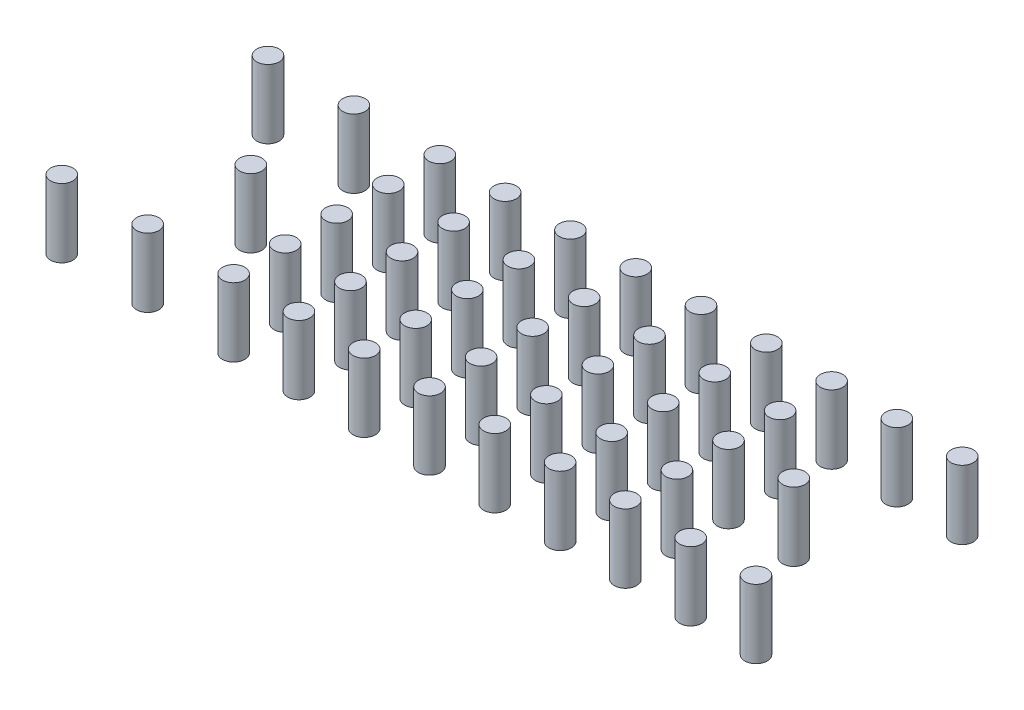
SolidWorks part; units mm, degrees
ref_plane "Front Plane" through (0, 0, 0) normal (0, 0, 1) x (1, 0, 0)
ref_plane "Top Plane" through (0, 0, 0) normal (0, 1, 0) x (1, 0, 0)
ref_plane "Right Plane" through (0, 0, 0) normal (1, 0, 0) x (0, 0, -1)
sketch "Sketch2" plane through (0, 0, 0) normal (0, 1, 0) x (1, 0, 0)
  line L0 (1.9, 0) -> (3.35, 0) construction
  line L1 (0, 0) -> (1.45, 0) construction
  line L2 (0, 0) -> (0, -1.25) construction
  line L3 (0, -1.25) -> (1.45, -1.25) construction
  line L4 (1.45, 0) -> (1.45, -1.25) construction
  line L5 (1.9, 0) -> (1.9, -1.25) construction
  line L6 (1.9, -1.25) -> (3.35, -1.25) construction
  line L7 (3.35, 0) -> (3.35, -1.25) construction
  line L8 (3.8, 0) -> (5.25, 0) construction
  line L9 (3.8, 0) -> (3.8, -1.25) construction
  line L10 (3.8, -1.25) -> (5.25, -1.25) construction
  line L11 (5.25, 0) -> (5.25, -1.25) construction
  line L12 (5.7, 0) -> (7.15, 0) construction
  line L13 (5.7, 0) -> (5.7, -1.25) construction
  line L14 (5.7, -1.25) -> (7.15, -1.25) construction
  line L15 (7.15, 0) -> (7.15, -1.25) construction
  line L16 (7.6, 0) -> (9.05, 0) construction
  line L17 (7.6, 0) -> (7.6, -1.25) construction
  line L18 (7.6, -1.25) -> (9.05, -1.25) construction
  line L19 (9.05, 0) -> (9.05, -1.25) construction
  line L20 (9.5, 0) -> (10.95, 0) construction
  line L21 (9.5, 0) -> (9.5, -1.25) construction
  line L22 (9.5, -1.25) -> (10.95, -1.25) construction
  line L23 (10.95, 0) -> (10.95, -1.25) construction
  line L24 (11.4, 0) -> (12.85, 0) construction
  line L25 (11.4, 0) -> (11.4, -1.25) construction
  line L26 (11.4, -1.25) -> (12.85, -1.25) construction
  line L27 (12.85, 0) -> (12.85, -1.25) construction
  line L28 (13.3, 0) -> (14.75, 0) construction
  line L29 (13.3, 0) -> (13.3, -1.25) construction
  line L30 (13.3, -1.25) -> (14.75, -1.25) construction
  line L31 (14.75, 0) -> (14.75, -1.25) construction
  line L32 (15.2, 0) -> (16.65, 0) construction
  line L33 (15.2, 0) -> (15.2, -1.25) construction
  line L34 (15.2, -1.25) -> (16.65, -1.25) construction
  line L35 (16.65, 0) -> (16.65, -1.25) construction
  line L36 (1.9, 1.5) -> (3.35, 1.5) construction
  line L37 (1.9, 1.5) -> (1.9, 0.25) construction
  line L38 (1.9, 0.25) -> (3.35, 0.25) construction
  line L39 (3.35, 1.5) -> (3.35, 0.25) construction
  line L40 (3.8, 1.5) -> (5.25, 1.5) construction
  line L41 (3.8, 1.5) -> (3.8, 0.25) construction
  line L42 (3.8, 0.25) -> (5.25, 0.25) construction
  line L43 (5.25, 1.5) -> (5.25, 0.25) construction
  line L44 (5.7, 1.5) -> (7.15, 1.5) construction
  line L45 (5.7, 1.5) -> (5.7, 0.25) construction
  line L46 (5.7, 0.25) -> (7.15, 0.25) construction
  line L47 (7.15, 1.5) -> (7.15, 0.25) construction
  line L48 (7.6, 1.5) -> (9.05, 1.5) construction
  line L49 (7.6, 1.5) -> (7.6, 0.25) construction
  line L50 (7.6, 0.25) -> (9.05, 0.25) construction
  line L51 (9.05, 1.5) -> (9.05, 0.25) construction
  line L52 (9.5, 1.5) -> (10.95, 1.5) construction
  line L53 (9.5, 1.5) -> (9.5, 0.25) construction
  line L54 (9.5, 0.25) -> (10.95, 0.25) construction
  line L55 (10.95, 1.5) -> (10.95, 0.25) construction
  line L56 (11.4, 1.5) -> (12.85, 1.5) construction
  line L57 (11.4, 1.5) -> (11.4, 0.25) construction
  line L58 (11.4, 0.25) -> (12.85, 0.25) construction
  line L59 (12.85, 1.5) -> (12.85, 0.25) construction
  line L60 (13.3, 1.5) -> (14.75, 1.5) [skipped]
  line L61 (13.3, 1.5) -> (13.3, 0.25) [skipped]
  line L62 (13.3, 0.25) -> (14.75, 0.25) [skipped]
  line L63 (14.75, 1.5) -> (14.75, 0.25) [skipped]
  line L64 (15.2, 1.5) -> (16.65, 1.5) [skipped]
  line L65 (15.2, 1.5) -> (15.2, 0.25) [skipped]
  line L66 (15.2, 0.25) -> (16.65, 0.25) [skipped]
  line L67 (16.65, 1.5) -> (16.65, 0.25) [skipped]
  line L68 (1.9, 3) -> (3.35, 3) construction
  line L69 (1.9, 3) -> (1.9, 1.75) construction
  line L70 (1.9, 1.75) -> (3.35, 1.75) construction
  line L71 (3.35, 3) -> (3.35, 1.75) construction
  line L72 (3.8, 3) -> (5.25, 3) construction
  line L73 (3.8, 3) -> (3.8, 1.75) construction
  line L74 (3.8, 1.75) -> (5.25, 1.75) construction
  line L75 (5.25, 3) -> (5.25, 1.75) construction
  line L76 (5.7, 3) -> (7.15, 3) construction
  line L77 (5.7, 3) -> (5.7, 1.75) construction
  line L78 (5.7, 1.75) -> (7.15, 1.75) construction
  line L79 (7.15, 3) -> (7.15, 1.75) construction
  line L80 (7.6, 3) -> (9.05, 3) construction
  line L81 (7.6, 3) -> (7.6, 1.75) construction
  line L82 (7.6, 1.75) -> (9.05, 1.75) construction
  line L83 (9.05, 3) -> (9.05, 1.75) construction
  line L84 (9.5, 3) -> (10.95, 3) construction
  line L85 (9.5, 3) -> (9.5, 1.75) construction
  line L86 (9.5, 1.75) -> (10.95, 1.75) construction
  line L87 (10.95, 3) -> (10.95, 1.75) construction
  line L88 (11.4, 3) -> (12.85, 3) construction
  line L89 (11.4, 3) -> (11.4, 1.75) construction
  line L90 (11.4, 1.75) -> (12.85, 1.75) construction
  line L91 (12.85, 3) -> (12.85, 1.75) construction
  line L92 (13.3, 3) -> (14.75, 3) construction
  line L93 (13.3, 3) -> (13.3, 1.75) construction
  line L94 (13.3, 1.75) -> (14.75, 1.75) construction
  line L95 (14.75, 3) -> (14.75, 1.75) construction
  line L96 (15.2, 3) -> (16.65, 3) [skipped]
  line L97 (15.2, 3) -> (15.2, 1.75) [skipped]
  line L98 (15.2, 1.75) -> (16.65, 1.75) [skipped]
  line L99 (16.65, 3) -> (16.65, 1.75) [skipped]
  line L100 (1.9, 4.5) -> (3.35, 4.5) construction
  line L101 (1.9, 4.5) -> (1.9, 3.25) construction
  line L102 (1.9, 3.25) -> (3.35, 3.25) construction
  line L103 (3.35, 4.5) -> (3.35, 3.25) construction
  line L104 (3.8, 4.5) -> (5.25, 4.5) construction
  line L105 (3.8, 4.5) -> (3.8, 3.25) construction
  line L106 (3.8, 3.25) -> (5.25, 3.25) construction
  line L107 (5.25, 4.5) -> (5.25, 3.25) construction
  line L108 (5.7, 4.5) -> (7.15, 4.5) construction
  line L109 (5.7, 4.5) -> (5.7, 3.25) construction
  line L110 (5.7, 3.25) -> (7.15, 3.25) construction
  line L111 (7.15, 4.5) -> (7.15, 3.25) construction
  line L112 (7.6, 4.5) -> (9.05, 4.5) construction
  line L113 (7.6, 4.5) -> (7.6, 3.25) construction
  line L114 (7.6, 3.25) -> (9.05, 3.25) construction
  line L115 (9.05, 4.5) -> (9.05, 3.25) construction
  line L116 (9.5, 4.5) -> (10.95, 4.5) construction
  line L117 (9.5, 4.5) -> (9.5, 3.25) construction
  line L118 (9.5, 3.25) -> (10.95, 3.25) construction
  line L119 (10.95, 4.5) -> (10.95, 3.25) construction
  line L120 (11.4, 4.5) -> (12.85, 4.5) construction
  line L121 (11.4, 4.5) -> (11.4, 3.25) construction
  line L122 (11.4, 3.25) -> (12.85, 3.25) construction
  line L123 (12.85, 4.5) -> (12.85, 3.25) construction
  line L124 (13.3, 4.5) -> (14.75, 4.5) [skipped]
  line L125 (13.3, 4.5) -> (13.3, 3.25) [skipped]
  line L126 (13.3, 3.25) -> (14.75, 3.25) [skipped]
  line L127 (14.75, 4.5) -> (14.75, 3.25) [skipped]
  line L128 (15.2, 4.5) -> (16.65, 4.5) [skipped]
  line L129 (15.2, 4.5) -> (15.2, 3.25) [skipped]
  line L130 (15.2, 3.25) -> (16.65, 3.25) [skipped]
  line L131 (16.65, 4.5) -> (16.65, 3.25) [skipped]
  line L132 (1.9, 6) -> (3.35, 6) construction
  line L133 (1.9, 6) -> (1.9, 4.75) construction
  line L134 (1.9, 4.75) -> (3.35, 4.75) construction
  line L135 (3.35, 6) -> (3.35, 4.75) construction
  line L136 (3.8, 6) -> (5.25, 6) construction
  line L137 (3.8, 6) -> (3.8, 4.75) construction
  line L138 (3.8, 4.75) -> (5.25, 4.75) construction
  line L139 (5.25, 6) -> (5.25, 4.75) construction
  line L140 (5.7, 6) -> (7.15, 6) construction
  line L141 (5.7, 6) -> (5.7, 4.75) construction
  line L142 (5.7, 4.75) -> (7.15, 4.75) construction
  line L143 (7.15, 6) -> (7.15, 4.75) construction
  line L144 (7.6, 6) -> (9.05, 6) construction
  line L145 (7.6, 6) -> (7.6, 4.75) construction
  line L146 (7.6, 4.75) -> (9.05, 4.75) construction
  line L147 (9.05, 6) -> (9.05, 4.75) construction
  line L148 (9.5, 6) -> (10.95, 6) construction
  line L149 (9.5, 6) -> (9.5, 4.75) construction
  line L150 (9.5, 4.75) -> (10.95, 4.75) construction
  line L151 (10.95, 6) -> (10.95, 4.75) construction
  line L152 (11.4, 6) -> (12.85, 6) construction
  line L153 (11.4, 6) -> (11.4, 4.75) construction
  line L154 (11.4, 4.75) -> (12.85, 4.75) construction
  line L155 (12.85, 6) -> (12.85, 4.75) construction
  line L156 (13.3, 6) -> (14.75, 6) construction
  line L157 (13.3, 6) -> (13.3, 4.75) construction
  line L158 (13.3, 4.75) -> (14.75, 4.75) construction
  line L159 (14.75, 6) -> (14.75, 4.75) construction
  line L160 (15.2, 6) -> (16.65, 6) construction
  line L161 (15.2, 6) -> (15.2, 4.75) construction
  line L162 (15.2, 4.75) -> (16.65, 4.75) construction
  line L163 (16.65, 6) -> (16.65, 4.75) construction
  line L164 (0, 1.5) -> (1.45, 1.5) construction
  line L165 (0, 1.5) -> (0, 0.25) construction
  line L166 (0, 0.25) -> (1.45, 0.25) construction
  line L167 (1.45, 1.5) -> (1.45, 0.25) construction
  line L168 (0, 3) -> (1.45, 3) construction
  line L169 (0, 3) -> (0, 1.75) construction
  line L170 (0, 1.75) -> (1.45, 1.75) construction
  line L171 (1.45, 3) -> (1.45, 1.75) construction
  line L172 (0, 4.5) -> (1.45, 4.5) construction
  line L173 (0, 4.5) -> (0, 3.25) construction
  line L174 (0, 3.25) -> (1.45, 3.25) construction
  line L175 (1.45, 4.5) -> (1.45, 3.25) construction
  line L176 (0, 6) -> (1.45, 6) construction
  line L177 (0, 6) -> (0, 4.75) construction
  line L178 (0, 4.75) -> (1.45, 4.75) construction
  line L179 (1.45, 6) -> (1.45, 4.75) construction
  line L180 (1.45, 0) -> (0, -1.25) construction
  line L181 (3.35, 0) -> (1.9, -1.25) construction
  line L182 (5.25, 0) -> (3.8, -1.25) construction
  line L183 (7.15, 0) -> (5.7, -1.25) construction
  line L184 (9.05, 0) -> (7.6, -1.25) construction
  line L185 (10.95, 0) -> (9.5, -1.25) construction
  line L186 (12.85, 0) -> (11.4, -1.25) construction
  line L187 (14.75, 0) -> (13.3, -1.25) construction
  line L188 (16.65, 0) -> (15.2, -1.25) construction
  line L189 (3.35, 1.5) -> (1.9, 0.25) construction
  line L190 (5.25, 1.5) -> (3.8, 0.25) construction
  line L191 (7.15, 1.5) -> (5.7, 0.25) construction
  line L192 (9.05, 1.5) -> (7.6, 0.25) construction
  line L193 (10.95, 1.5) -> (9.5, 0.25) construction
  line L194 (12.85, 1.5) -> (11.4, 0.25) construction
  line L195 (-1.05, 0) -> (-2.5, -1.25) construction
  line L196 (-1.05, -1.25) -> (-2.5, -1.25) construction
  line L197 (3.35, 3) -> (1.9, 1.75) construction
  line L198 (5.25, 3) -> (3.8, 1.75) construction
  line L199 (7.15, 3) -> (5.7, 1.75) construction
  line L200 (9.05, 3) -> (7.6, 1.75) construction
  line L201 (10.95, 3) -> (9.5, 1.75) construction
  line L202 (12.85, 3) -> (11.4, 1.75) construction
  line L203 (14.75, 3) -> (13.3, 1.75) construction
  line L204 (-1.05, -1.25) -> (-1.05, 0) construction
  line L205 (3.35, 4.5) -> (1.9, 3.25) construction
  line L206 (5.25, 4.5) -> (3.8, 3.25) construction
  line L207 (7.15, 4.5) -> (5.7, 3.25) construction
  line L208 (9.05, 4.5) -> (7.6, 3.25) construction
  line L209 (10.95, 4.5) -> (9.5, 3.25) construction
  line L210 (12.85, 4.5) -> (11.4, 3.25) construction
  line L211 (-1.05, 0) -> (-2.5, 0) construction
  line L212 (-2.5, -1.25) -> (-2.5, 0) construction
  line L213 (3.35, 6) -> (1.9, 4.75) construction
  line L214 (5.25, 6) -> (3.8, 4.75) construction
  line L215 (7.15, 6) -> (5.7, 4.75) construction
  line L216 (9.05, 6) -> (7.6, 4.75) construction
  line L217 (10.95, 6) -> (9.5, 4.75) construction
  line L218 (12.85, 6) -> (11.4, 4.75) construction
  line L219 (14.75, 6) -> (13.3, 4.75) construction
  line L220 (16.65, 6) -> (15.2, 4.75) construction
  line L221 (1.45, 1.5) -> (0, 0.25) construction
  line L222 (1.45, 3) -> (0, 1.75) construction
  line L223 (1.45, 4.5) -> (0, 3.25) construction
  line L224 (1.45, 6) -> (0, 4.75) construction
  line L225 (14.75, 1.5) -> (13.3, 0.25) construction
  line L226 (16.65, 1.5) -> (15.2, 0.25) construction
  line L227 (16.65, 3) -> (15.2, 1.75) construction
  line L228 (14.75, 4.5) -> (13.3, 3.25) construction
  line L229 (16.65, 4.5) -> (15.2, 3.25) construction
  line L230 (-3.55, 0) -> (-5, -1.25) construction
  line L231 (-3.55, -1.25) -> (-5, -1.25) construction
  line L232 (-3.55, -1.25) -> (-3.55, 0) construction
  line L233 (-3.55, 0) -> (-5, 0) construction
  line L234 (-5, -1.25) -> (-5, 0) construction
  line L235 (-3.55, 1.5) -> (-5, 0.25) construction
  line L236 (-3.55, 0.25) -> (-5, 0.25) construction
  line L237 (-3.55, 0.25) -> (-3.55, 1.5) construction
  line L238 (-3.55, 1.5) -> (-5, 1.5) construction
  line L239 (-5, 0.25) -> (-5, 1.5) construction
  line L240 (-3.55, 3) -> (-5, 1.75) construction
  line L241 (-3.55, 1.75) -> (-5, 1.75) construction
  line L242 (-3.55, 1.75) -> (-3.55, 3) construction
  line L243 (-3.55, 3) -> (-5, 3) construction
  line L244 (-5, 1.75) -> (-5, 3) construction
  line L245 (-3.55, 4.5) -> (-5, 3.25) construction
  line L246 (-3.55, 3.25) -> (-5, 3.25) construction
  line L247 (-3.55, 3.25) -> (-3.55, 4.5) construction
  line L248 (-3.55, 4.5) -> (-5, 4.5) construction
  line L249 (-5, 3.25) -> (-5, 4.5) construction
  line L250 (-3.55, 6) -> (-5, 4.75) construction
  line L251 (-3.55, 4.75) -> (-5, 4.75) construction
  line L252 (-3.55, 4.75) -> (-3.55, 6) construction
  line L253 (-3.55, 6) -> (-5, 6) construction
  line L254 (-5, 4.75) -> (-5, 6) construction
  line L255 (-1.05, 1.5) -> (-2.5, 0.25) construction
  line L256 (-1.05, 0.25) -> (-2.5, 0.25) construction
  line L257 (-1.05, 0.25) -> (-1.05, 1.5) construction
  line L258 (-1.05, 1.5) -> (-2.5, 1.5) construction
  line L259 (-2.5, 0.25) -> (-2.5, 1.5) construction
  line L260 (-1.05, 3) -> (-2.5, 1.75) construction
  line L261 (-1.05, 1.75) -> (-2.5, 1.75) construction
  line L262 (-1.05, 1.75) -> (-1.05, 3) construction
  line L263 (-1.05, 3) -> (-2.5, 3) construction
  line L264 (-2.5, 1.75) -> (-2.5, 3) construction
  line L265 (-1.05, 4.5) -> (-2.5, 3.25) construction
  line L266 (-1.05, 3.25) -> (-2.5, 3.25) construction
  line L267 (-1.05, 3.25) -> (-1.05, 4.5) construction
  line L268 (-1.05, 4.5) -> (-2.5, 4.5) construction
  line L269 (-2.5, 3.25) -> (-2.5, 4.5) construction
  line L270 (-1.05, 6) -> (-2.5, 4.75) construction
  line L271 (-1.05, 4.75) -> (-2.5, 4.75) construction
  line L272 (-1.05, 4.75) -> (-1.05, 6) construction
  line L273 (-1.05, 6) -> (-2.5, 6) construction
  line L274 (-2.5, 4.75) -> (-2.5, 6) construction
  circle A0 centre (0.725, -0.625) radius 0.325
  circle A1 centre (2.625, -0.625) radius 0.325
  circle A2 centre (4.525, -0.625) radius 0.325
  circle A3 centre (6.425, -0.625) radius 0.325
  circle A4 centre (8.325, -0.625) radius 0.325
  circle A5 centre (10.225, -0.625) radius 0.325
  circle A6 centre (12.125, -0.625) radius 0.325
  circle A7 centre (14.025, -0.625) radius 0.325
  circle A8 centre (15.925, -0.625) radius 0.325
  circle A9 centre (2.625, 0.875) radius 0.325
  circle A10 centre (4.525, 0.875) radius 0.325
  circle A11 centre (6.425, 0.875) radius 0.325
  circle A12 centre (8.325, 0.875) radius 0.325
  circle A13 centre (10.225, 0.875) radius 0.325
  circle A14 centre (12.125, 0.875) radius 0.325
  circle A17 centre (2.625, 2.375) radius 0.325
  circle A18 centre (4.525, 2.375) radius 0.325
  circle A19 centre (6.425, 2.375) radius 0.325
  circle A20 centre (8.325, 2.375) radius 0.325
  circle A21 centre (10.225, 2.375) radius 0.325
  circle A22 centre (12.125, 2.375) radius 0.325
  circle A23 centre (14.025, 2.375) radius 0.325
  circle A25 centre (2.625, 3.875) radius 0.325
  circle A26 centre (4.525, 3.875) radius 0.325
  circle A27 centre (6.425, 3.875) radius 0.325
  circle A28 centre (8.325, 3.875) radius 0.325
  circle A29 centre (10.225, 3.875) radius 0.325
  circle A30 centre (12.125, 3.875) radius 0.325
  circle A33 centre (2.625, 5.375) radius 0.325
  circle A34 centre (4.525, 5.375) radius 0.325
  circle A35 centre (6.425, 5.375) radius 0.325
  circle A36 centre (8.325, 5.375) radius 0.325
  circle A37 centre (10.225, 5.375) radius 0.325
  circle A38 centre (12.125, 5.375) radius 0.325
  circle A39 centre (14.025, 5.375) radius 0.325
  circle A40 centre (15.925, 5.375) radius 0.325
  circle A41 centre (0.725, 0.875) radius 0.325
  circle A42 centre (0.725, 2.375) radius 0.325
  circle A43 centre (0.725, 3.875) radius 0.325
  circle A44 centre (0.725, 5.375) radius 0.325
  circle A45 centre (14.025, 0.875) radius 0.325 [skipped]
  circle A46 centre (15.925, 0.875) radius 0.325 [skipped]
  circle A47 centre (15.925, 2.375) radius 0.325 [skipped]
  circle A48 centre (14.025, 3.875) radius 0.325 [skipped]
  circle A49 centre (15.925, 3.875) radius 0.325 [skipped]
  circle A50 centre (-1.775, -0.625) radius 0.325
  circle A51 centre (-4.275, -0.625) radius 0.325
  circle A52 centre (-4.275, 0.875) radius 0.325 [skipped]
  circle A53 centre (-4.275, 2.375) radius 0.325 [skipped]
  circle A54 centre (-4.275, 3.875) radius 0.325 [skipped]
  circle A55 centre (-4.275, 5.375) radius 0.325
  circle A56 centre (-1.775, 0.875) radius 0.325 [skipped]
  circle A57 centre (-1.775, 2.375) radius 0.325
  circle A58 centre (-1.775, 3.875) radius 0.325 [skipped]
  circle A59 centre (-1.775, 5.375) radius 0.325
  dimension "D5" = 0.65
  dimension "D11" = 0.65
  dimension "D1" = 1.45
  dimension "D2" = 1.25
  dimension "D6" = 1.5
  dimension "D7" = 1.9
  dimension "D8" = 1.05
  dimension "D9" = 1.25
  dimension "D10" = 1.45
  dimension "D3" = 9
  dimension "D4" = 5
  dimension "D12" = 2
  dimension "D13" = 5
extrude "Boss-Extrude1" add sketch "Sketch2" along normal blind 2
